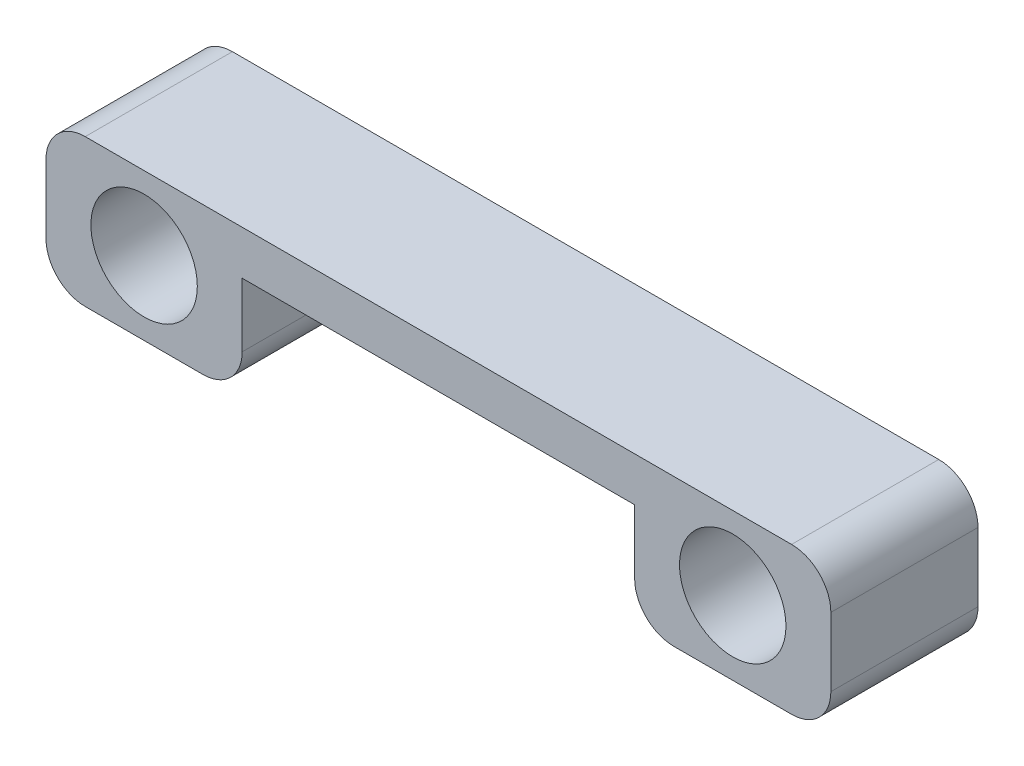
SolidWorks part; units mm, degrees
ref_plane "Front Plane" through (0, 0, 0) normal (0, 0, 1) x (1, 0, 0)
ref_plane "Top Plane" through (0, 0, 0) normal (0, 1, 0) x (1, 0, 0)
ref_plane "Right Plane" through (0, 0, 0) normal (1, 0, 0) x (0, 0, -1)
sketch "Sketch2" plane through (0, 0, 0) normal (0, 0, 1) x (1, 0, 0)
  line L0 (20, 30) -> (20, 0) construction
  line L1 (8, 0) -> (32, 0)
  line L4 (40, 8) -> (40, 30)
  line L5 (0, 22) -> (0, 8)
  line L6 (8, 30) -> (40, 30)
  line L7 (80, 30) -> (80, -4.8933) construction
  line L8 (40, 30) -> (120, 30)
  line L9 (40, 30) -> (40, 21)
  line L10 (40, 21) -> (120, 21)
  line L11 (120, 30) -> (120, 21)
  line L12 (120, 8) -> (120, 30)
  line L13 (152, 0) -> (128, 0)
  line L14 (160, 22) -> (160, 8)
  line L15 (152, 30) -> (120, 30)
  circle A0 centre (20, 15) radius 10.85
  arc A2 (0, 22) -> (8, 30) centre (8, 22) cw
  arc A3 (32, 0) -> (40, 8) centre (32, 8) ccw
  arc A4 (8, 0) -> (0, 8) centre (8, 8) cw
  arc A5 (128, 0) -> (120, 8) centre (128, 8) cw
  arc A6 (152, 0) -> (160, 8) centre (152, 8) ccw
  arc A7 (160, 22) -> (152, 30) centre (152, 22) ccw
  circle A8 centre (140, 15) radius 10.85
  point P19 (40, 0)
  point P22 (0, 0)
  dimension "D1" = 21.7
  dimension "D7" = 8
  dimension "D5" = 40
  dimension "D6" = 9
  dimension "D9" = 160
  dimension "D10" = 40
extrude "Boss-Extrude1" add sketch "Sketch2" along normal blind 30
